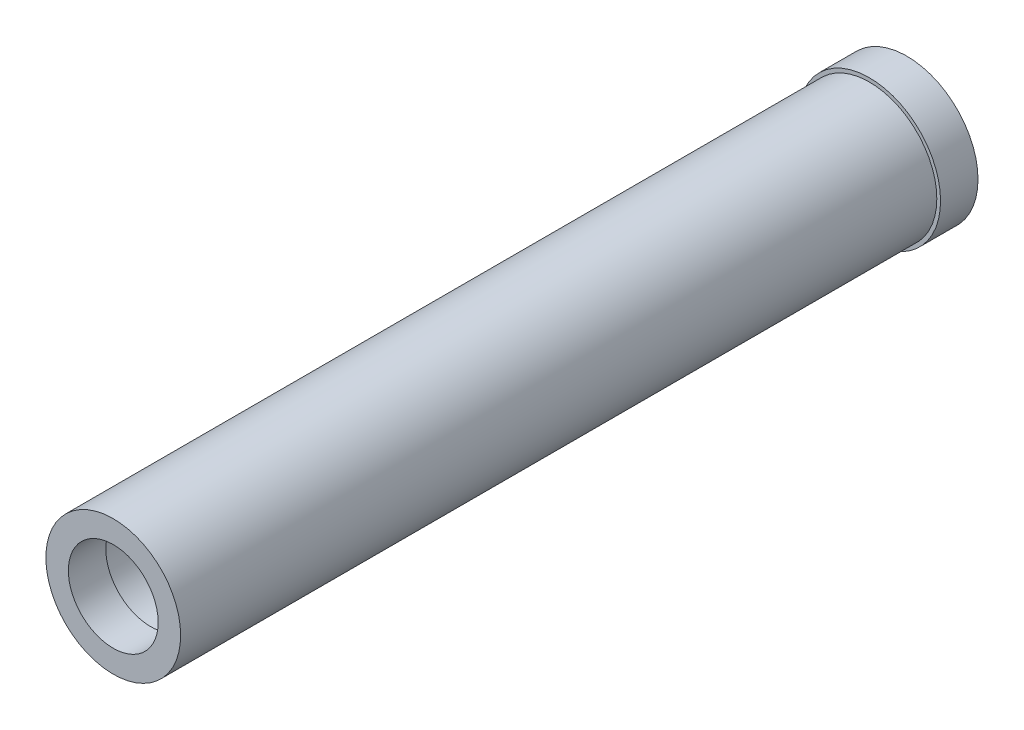
SolidWorks part; units mm, degrees
ref_plane "Front Plane" through (0, 0, 0) normal (0, 0, 1) x (1, 0, 0)
ref_plane "Top Plane" through (0, 0, 0) normal (0, 1, 0) x (1, 0, 0)
ref_plane "Right Plane" through (0, 0, 0) normal (1, 0, 0) x (0, 0, -1)
sketch "Sketch1" plane through (0, 0, 0) normal (0, 0, 1) x (1, 0, 0)
  circle A0 centre (0, 0) radius 19
  circle A1 centre (0, 0) radius 18
  dimension "D1" = 38
  dimension "D2" = 36
extrude "Boss-Extrude2" add sketch "Sketch1" along normal blind 10 contours A0 A1
sketch "Sketch2" plane through (0, 0, 10) normal (0, 0, 1) x (1, 0, 0)
  circle A0 centre (0, 0) radius 18
  dimension "D1" = 36
extrude "Boss-Extrude3" add sketch "Sketch2" along normal blind 202
sketch "Sketch3" plane through (0, 0, 212) normal (0, 0, 1) x (1, 0, 0)
  circle A0 centre (0, 0) radius 13
  dimension "D1" = 26
extrude "Cut-Extrude1" cut sketch "Sketch3" against normal blind 200
sketch "Sketch4" plane through (0, 0, 212) normal (0, 0, 1) x (1, 0, 0)
  circle A0 centre (0, 0) radius 12
  circle A1 centre (0, 0) radius 13 construction
  circle A2 centre (0, 0) radius 13
  dimension "D1" = 24
extrude "Boss-Extrude4" add sketch "Sketch4" against normal blind 10
